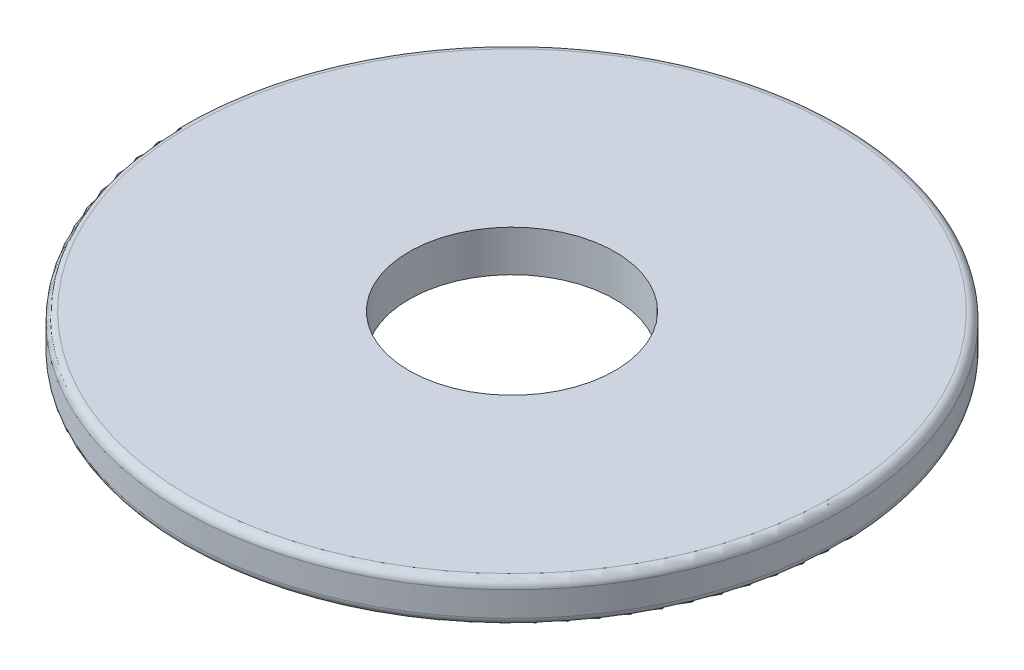
SolidWorks part; units mm, degrees
ref_plane "前视基准面" through (0, 0, 0) normal (0, 0, 1) x (1, 0, 0)
ref_plane "上视基准面" through (0, 0, 0) normal (0, 1, 0) x (1, 0, 0)
ref_plane "右视基准面" through (0, 0, 0) normal (1, 0, 0) x (0, 0, -1)
sketch "Sketch1" plane through (0, 0, 0) normal (0, 1, 0) x (1, 0, 0)
  circle A0 centre (0, 0) radius 8
  circle A1 centre (0, 0) radius 2.5
  dimension "D1" = 5
  dimension "D2" = 16
extrude "Boss-Extrude1" add sketch "Sketch1" along normal blind 1
fillet "Fillet1" radius 0.2 2 edges at (0, 0, 8) (0, 1, 8)
